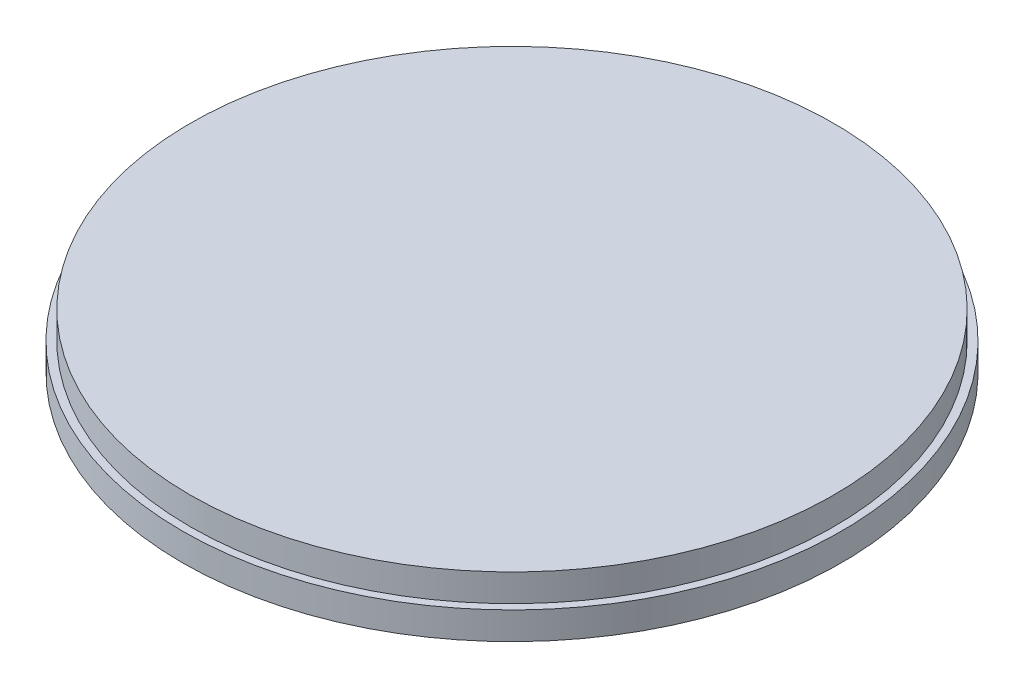
SolidWorks part; units mm, degrees
ref_plane "Front Plane" through (0, 0, 0) normal (0, 0, 1) x (1, 0, 0)
ref_plane "Top Plane" through (0, 0, 0) normal (0, 1, 0) x (1, 0, 0)
ref_plane "Right Plane" through (0, 0, 0) normal (1, 0, 0) x (0, 0, -1)
sketch "Sketch1" plane through (0, 0, 0) normal (0, 1, 0) x (1, 0, 0)
  circle A0 centre (0, 0) radius 76.2
  dimension "D1" = 152.4
extrude "Boss-Extrude1" add sketch "Sketch1" along normal blind 6.35
sketch "Sketch2" plane through (0, 6.35, 0) normal (0, 1, 0) x (1, 0, 0)
  circle A0 centre (0, 0) radius 74.422
  dimension "D1" = 148.844
extrude "Boss-Extrude2" add sketch "Sketch2" along normal blind 6.35
